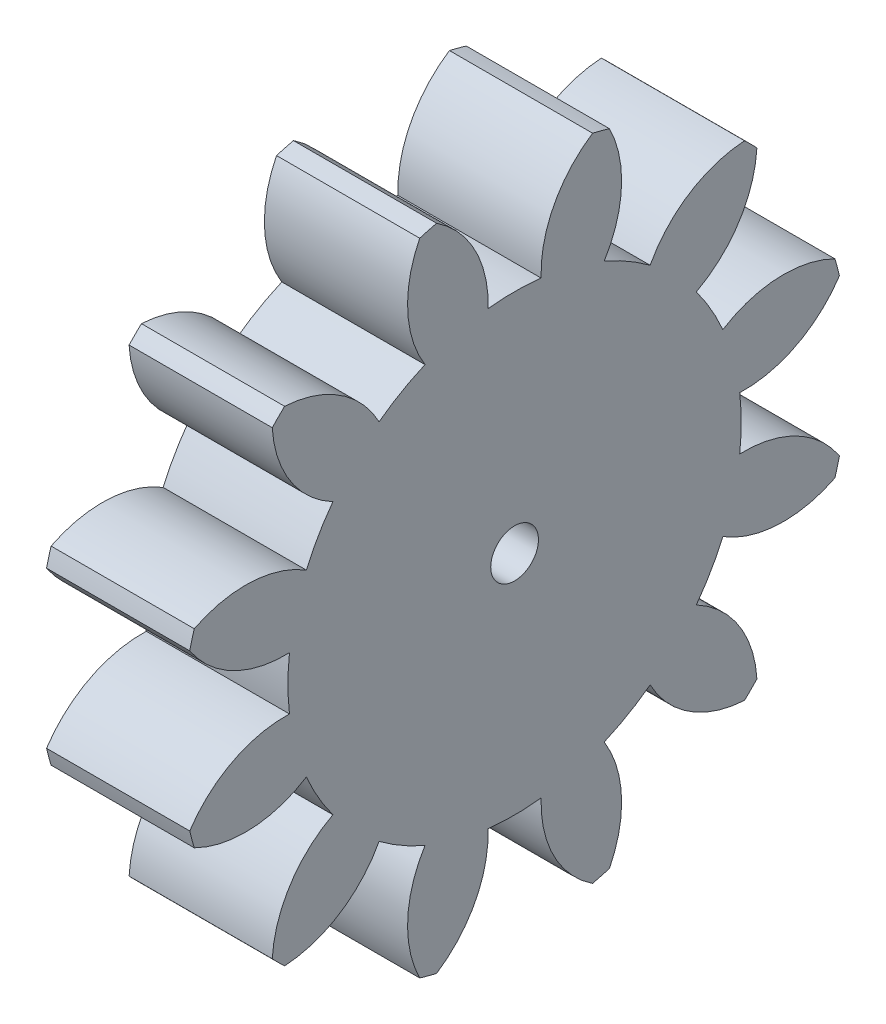
SolidWorks part; units mm, degrees
ref_plane "Plane1" through (0, 0, 0) normal (0, 0, 1) x (1, 0, 0)
ref_plane "Plane2" through (0, 0, 0) normal (0, 1, 0) x (1, 0, 0)
ref_plane "Plane3" through (0, 0, 0) normal (1, 0, 0) x (0, 0, -1)
other "Configuration Table"
sketch "HoldingSke" plane through (0, 0, 0) normal (0, 1, 0) x (1, 0, 0)
  line L0 (0, 0) -> (0.1956, -0.0416)
  line L1 (-15, 0) -> (100, 0) construction
  line L2 (0, 0) -> (-2.1039, 2.3779)
  line L3 (0, 0) -> (-11.863, 4.5341)
  line L4 (0, 0) -> (8.4473, 1.7955)
  line L5 (0, 0) -> (-46.8476, -17.4728)
  line L6 (0, 0) -> (-12.4344, -8.3896)
  line L7 (-2.1039, 2.3779) -> (8.6586, 51.2059)
  line L8 (-76.2, 54.61) -> (-75.3, 54.61)
  line L9 (-71.009, 38.7566) -> (-53.1078, 45.2721)
  line L10 (-76.2, 71.12) -> (104.1128, 71.12)
  line L11 (0, 0) -> (-15, 0)
  line L12 (-76.2, 101.6) -> (-76.033, 101.6)
  line L13 (24.9733, 27.94) -> (52.9518, 28.4284)
  line L14 (24.9733, 27.94) -> (24.9743, 27.94)
  line L15 (24.9733, 27.94) -> (100.4006, 29.5858)
  line L16 (-63.627, -5) -> (-12.827, -5)
  circle A0 centre (0, 0) radius 2.5
  circle A1 centre (0, 0) radius 23.749
  circle A2 centre (0, 0) radius 37.5
  circle A3 centre (0, 0) radius 2.5
  dimension "Hub_dia" = 75
  dimension "Bore" = 5
  dimension "MBD" = 5
  dimension "Pitch" = 0.2
  dimension "Overall_len" = 50
  dimension "Thickness" = 15
  dimension "OAL" = 50.0001
  dimension "T_dim" = 0.9
  dimension "Ap" = 20
  dimension "H" = 19.05
  dimension "Pitch_radius" = 180.3128
  dimension "Width" = 15
  dimension "Backlash" = 0.167
  dimension "Addendum_fac" = 1
  dimension "Dedendum_fac" = 1.25
  dimension "Clearance_fac" = 0.25
  dimension "Dedendum_add" = 0.001
  dimension "Module" = 5
sketch "BasProSke" plane through (0, 0, 0) normal (0, 1, 0) x (1, 0, 0)
  line L0 (-10, 0) -> (60, 0) construction
  line L1 (0, 0) -> (0, 35)
  line L2 (0, 0) -> (15, 0)
  line L3 (15, 0) -> (15, 35)
  line L4 (15, 35) -> (0, 35)
  dimension "Thickness" = 15
revolve "Base-Revolve" add sketch "BasProSke" angle 360 about L0
sketch "TooCutSke" plane through (0, 0, 0) normal (1, 0, 0) x (0, 0, -1)
  line L1 (0, 0) -> (0, 107) construction
  line L2 (0, 0) -> (-4.2077, 29.7035) construction
  line L3 (0, 0) -> (-15.4154, 57.5312) construction
  line L4 (-4.2077, 29.7035) -> (-7.7077, 28.7656) construction
  arc A0 (2.779, 23.5858) -> (-2.779, 23.5858) centre (0, 0) ccw
  arc A1 (8.2005, 34.0519) -> (-8.2005, 34.0519) centre (0, 0) ccw
  circle A2 centre (0, 0) radius 30 construction
  circle A3 centre (0, 0) radius 28.1908 construction
  arc A4 (-2.779, 23.5858) -> (-8.2005, 34.0519) centre (-14.7715, 24.0109) ccw
  arc A5 (8.2005, 34.0519) -> (2.779, 23.5858) centre (14.7715, 24.0109) ccw
extrude "ToothCut" cut sketch "TooCutSke" along normal through all
fillet "Breaks" [suppressed] radius 0.1
fillet "RootFillets" [suppressed] radius 1.251
pattern_circular "TeethCuts" count 12 every 30 about axis through (-10, 0, 0) along (1, 0, 0) of "ToothCut", "RootFillets", "Breaks"
sketch "HubNeaOneSke" plane through (0, 0, 0) normal (-1, 0, 0) x (0, 0, 1)
  circle A0 centre (0, 0) radius 23.749
extrude "HubNearOne" [suppressed] add sketch "HubNeaOneSke" along normal blind 35.0001
sketch "HubNeaBotSke" plane through (0, 0, 0) normal (-1, 0, 0) x (0, 0, 1)
  circle A0 centre (0, 0) radius 23.749
extrude "HubNearBoth" [suppressed] add sketch "HubNeaBotSke" along normal blind 17.5
ref_plane "FarPln" through (15, 0, 0) normal (1, 0, 0) x (0, 0, -1)
sketch "HubFarSke" plane through (15, 0, 0) normal (1, 0, 0) x (0, 0, -1)
  circle A0 centre (0, 0) radius 23.749
extrude "HubFar" [suppressed] add sketch "HubFarSke" along normal blind 17.5
sketch "BorSke" plane through (0, 0, 0) normal (1, 0, 0) x (0, 0, -1)
  circle A0 centre (0, 0) radius 2.5
  dimension "Diameter" = 5
extrude "Bore" cut sketch "BorSke" along normal mid plane 100.0001
sketch "KeySke" plane through (0, 0, 0) normal (1, 0, 0) x (0, 0, -1)
  line L0 (-1, 0) -> (-1, 3.4)
  line L1 (-1, 3.4) -> (1, 3.4)
  line L2 (1, 3.4) -> (1, 0)
  line L3 (0, 0) -> (0, 34) construction
  line L4 (-1, 0) -> (1, 0)
  dimension "Offset" = 3.4
  dimension "Width" = 2
extrude "Keyway" [suppressed] cut sketch "KeySke" along normal mid plane 100.0001
pattern_circular "Keyway2" [suppressed] count 2 every 90 about axis through (-10, 0, 0) along (1, 0, 0)
equation "' \"Module@HoldingSke\" = 6.35"
equation "' \"Num_teeth@HoldingSke\" = 12"
equation "' \"Ap@HoldingSke\" =  20"
equation "' \"Ap@HoldingSke\" = 20"
equation "' \"Width@HoldingSke\" = 0.5 * 25.4"
equation "' \"Hub_dia@HoldingSke\"= 1 * 25.4"
equation "' \"Hub_dia@HoldingSke\" = 1 * 25.4"
equation "' \"Overall_len@HoldingSke\" = 1.0 * 25.4"
equation "' \"Bore@HoldingSke\" = 0.75 * 25.4"
equation "' \"T_dim@HoldingSke\" = 0.1 * 25.4"
equation "' \"Width@KeySke\" = 0.25 * 25.4"
equation "' \"Show_teeth@HoldingSke\" = 13"
equation "' \"Backlash@HoldingSke\" = 0.009 * 25.4"
equation "' \"Addendum_fac@HoldingSke\" = 1.0"
equation "' \"Dedendum_fac@HoldingSke\" = 1.25"
equation "' \"Dedendum_add@HoldingSke\" = 0.00005 * 25.4"
equation "' \"Clearance_fac@HoldingSke\" = 0.25"
equation "\"Pitch@HoldingSke\" = 1 / \"Module@HoldingSke\""
equation "\"Overcut_dia@TooCutSke\" = (\"Num_teeth@HoldingSke\" + 2 * \"Addendum_fac@HoldingSke\") / \"Pitch@HoldingSke\" + 0.002 * 25.4"
equation "\"Pitch_dia@TooCutSke\" = \"Num_teeth@HoldingSke\" / \"Pitch@HoldingSke\""
equation "\"Base_dia@TooCutSke\" = \"Num_teeth@HoldingSke\" / \"Pitch@HoldingSke\" * cos((\"Ap@HoldingSke\"  * 3.14159265 / 180))"
equation "\"Root_dia@TooCutSke\" = (\"Num_teeth@HoldingSke\" + 2) / \"Pitch@HoldingSke\" - 2 * (\"Addendum_fac@HoldingSke\" + \"Dedendum_fac@HoldingSke\") / \"Pitch@HoldingSke\" - \"Dedendum_add@HoldingSke\" * 2"
equation "\"Half_ang@TooCutSke\" = 180 / \"Num_teeth@HoldingSke\""
equation "\"Half_CT@TooCutSke\" = \"Num_teeth@HoldingSke\" / \"Pitch@HoldingSke\" * sin((3.14159265 / 2 / \"Num_teeth@HoldingSke\")) / 2 - 7 * \"Backlash@HoldingSke\" / 4"
equation "\"Flank_rad@TooCutSke\" = \"Num_teeth@HoldingSke\" / \"Pitch@HoldingSke\" / 5"
equation "\"Radius@RootFillets\" = \"Clearance_fac@HoldingSke\" / \"Pitch@HoldingSke\" + \"Dedendum_add@HoldingSke\""
equation "\"Break_rad@Breaks\" = 0.02 / \"Pitch@HoldingSke\""
equation "\"Thickness@HoldingSke\" = \"Width@HoldingSke\""
equation "\"OAL@HoldingSke\" = \"Thickness@HoldingSke\""
equation "\"MHD@HoldingSke\" = (\"Num_teeth@HoldingSke\" + 2) / \"Pitch@HoldingSke\" - 2 * (\"Addendum_fac@HoldingSke\" + \"Dedendum_fac@HoldingSke\")  / \"Pitch@HoldingSke\" - \"Dedendum_add@HoldingSke\" * 2"
equation "\"MBD@HoldingSke\" = (\"Num_teeth@HoldingSke\" + 2) / \"Pitch@HoldingSke\" - 2 * (\"Addendum_fac@HoldingSke\" + \"Dedendum_fac@HoldingSke\")  / \"Pitch@HoldingSke\" - \"Dedendum_add@HoldingSke\" * 2 - 0.002 * 25.4"
equation "\"MHD@HoldingSke\" = ((sgn( \"MHD@HoldingSke\" - \"Hub_dia@HoldingSke\" )-1)*( \"MHD@HoldingSke\" - \"Hub_dia@HoldingSke\" ))/-2+ \"Hub_dia@HoldingSke\""
equation "\"MBD@HoldingSke\" = ((sgn( \"MBD@HoldingSke\" - \"Bore@HoldingSke\" )-1)*( \"MBD@HoldingSke\" - \"Bore@HoldingSke\" ))/-2+ \"Bore@HoldingSke\""
equation "\"OAL@HoldingSke\" = ((sgn( \"OAL@HoldingSke\" - \"Overall_len@HoldingSke\" )+1)*( \"OAL@HoldingSke\" - \"Overall_len@HoldingSke\" ))/2 + \"Overall_len@HoldingSke\" + 0.000002 * 25.4"
equation "\"Num_teeth@TeethCuts\" = int( \"Show_teeth@HoldingSke\" ) + 1"
equation "\"Num_teeth@TeethCuts\" = ((sgn( \"Num_teeth@TeethCuts\" - \"Num_teeth@HoldingSke\" )-1)*( \"Num_teeth@TeethCuts\" - \"Num_teeth@HoldingSke\" ))/-2+ \"Num_teeth@HoldingSke\""
equation "\"Num_teeth@TeethCuts\" = ((sgn( \"Num_teeth@TeethCuts\" - 2.0)+1)*( \"Num_teeth@TeethCuts\" - 2.0))/2 +2.0"
equation "\"Angle@TeethCuts\" = 360.0 / \"Num_teeth@HoldingSke\""
equation "\"Diameter@BasProSke\" = (\"Num_teeth@HoldingSke\" + 2 * \"Addendum_fac@HoldingSke\") / \"Pitch@HoldingSke\""
equation "\"Thickness@BasProSke\"  = \"Thickness@HoldingSke\""
equation "' \"Fillet_rad@BasProSke\" =  \"Thickness@HoldingSke\" * 0.05"
equation "' \"Fillet_rad@BasProSke\" = \"Thickness@HoldingSke\" * 0.05"
equation "\"MHD@HoldingSke\" = ((sgn( \"MHD@HoldingSke\" - \"Root_dia@TooCutSke\" )-1)*( \"MHD@HoldingSke\" - \"Root_dia@TooCutSke\" ))/-2+ \"Root_dia@TooCutSke\""
equation "\"Diameter@HubNeaOneSke\" = \"MHD@HoldingSke\""
equation "\"Length@HubNearOne\" = \"OAL@HoldingSke\" - \"Thickness@BasProSke\""
equation "\"Diameter@HubNeaBotSke\" = \"MHD@HoldingSke\""
equation "\"Length@HubNearBoth\" = ( \"OAL@HoldingSke\" - \"Thickness@BasProSke\" ) / 2.0"
equation "\"Thickness@FarPln\" = \"Thickness@BasProSke\""
equation "\"Diameter@HubFarSke\" = \"MHD@HoldingSke\""
equation "\"Length@HubFar\" = ( \"OAL@HoldingSke\" - \"Thickness@BasProSke\" ) / 2.0"
equation "\"Diameter@BorSke\" = \"MBD@HoldingSke\""
equation "\"D1@Bore\" = \"OAL@HoldingSke\" * 2.0"
equation "\"D1@Keyway\" = \"OAL@HoldingSke\" * 2.0"
equation "\"Offset@KeySke\" = \"T_dim@HoldingSke\" + \"MBD@HoldingSke\" / 2.0"
